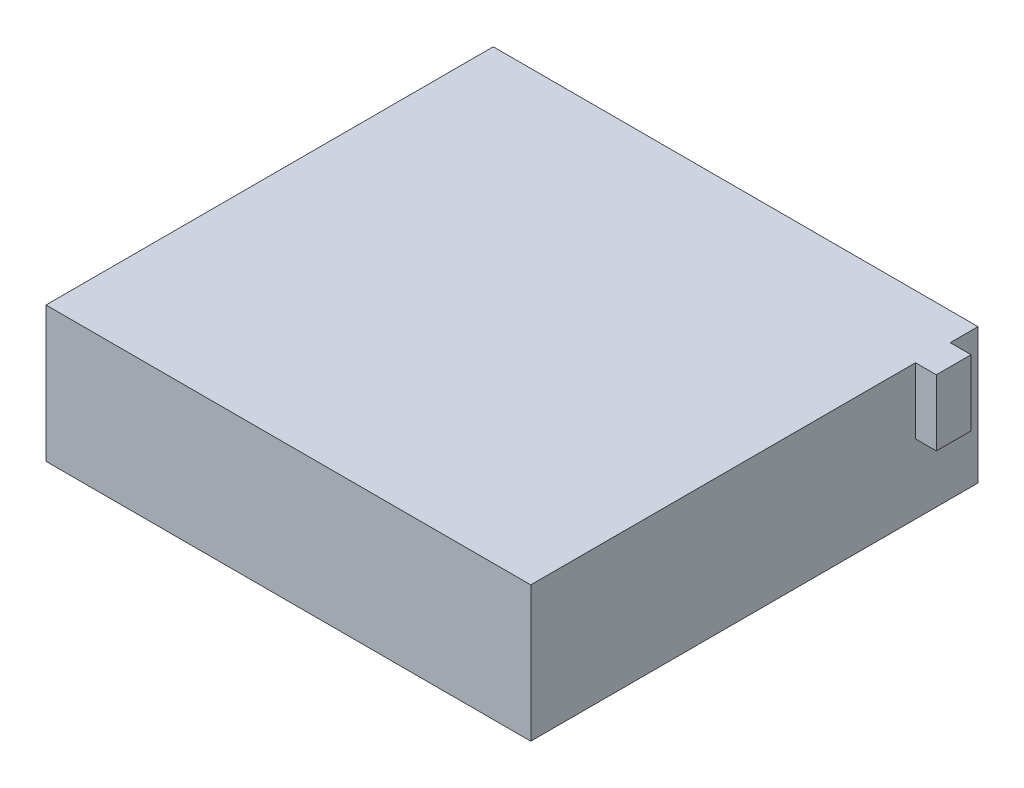
SolidWorks part; units mm, degrees
ref_plane "Front Plane" through (0, 0, 0) normal (0, 0, 1) x (1, 0, 0)
ref_plane "Top Plane" through (0, 0, 0) normal (0, 1, 0) x (1, 0, 0)
ref_plane "Right Plane" through (0, 0, 0) normal (1, 0, 0) x (0, 0, -1)
sketch "Sketch1" plane through (0, 0, 0) normal (0, 1, 0) x (1, 0, 0)
  line L1 (-34.9, 32.2) -> (34.9, 32.2)
  line L2 (-34.9, 32.2) -> (-34.9, -32.2)
  line L3 (-34.9, -32.2) -> (34.9, -32.2)
  line L4 (34.9, 32.2) -> (34.9, -32.2)
  line L5 (-34.9, 32.2) -> (34.9, -32.2) construction
  line L6 (-34.9, -32.2) -> (34.9, 32.2) construction
  point P0 (0, 0)
  dimension "D1" = 69.8
  dimension "D2" = 64.4
extrude "Boss-Extrude1" add sketch "Sketch1" along normal blind 19.5
sketch "Sketch2" plane through (34.9, 0, 0) normal (1, 0, 0) x (0, 0, -1)
  line L0 (-32.2, 19.5) -> (32.2, 19.5) construction
  line L1 (23.2, 19.5) -> (28.2, 19.5)
  line L2 (23.2, 19.5) -> (23.2, 10)
  line L3 (23.2, 10) -> (28.2, 10)
  line L4 (28.2, 19.5) -> (28.2, 10)
  line L5 (32.2, 19.5) -> (32.2, 0) construction
  line L6 (-32.2, 0) -> (32.2, 0) construction
  dimension "D1" = 9
  dimension "D2" = 10
  dimension "D3" = 5
extrude "Boss-Extrude2" add sketch "Sketch2" along normal blind 3
ref_plane "Plane1" through (0, 9.75, 0) normal (0, 1, 0) x (1, 0, 0)
